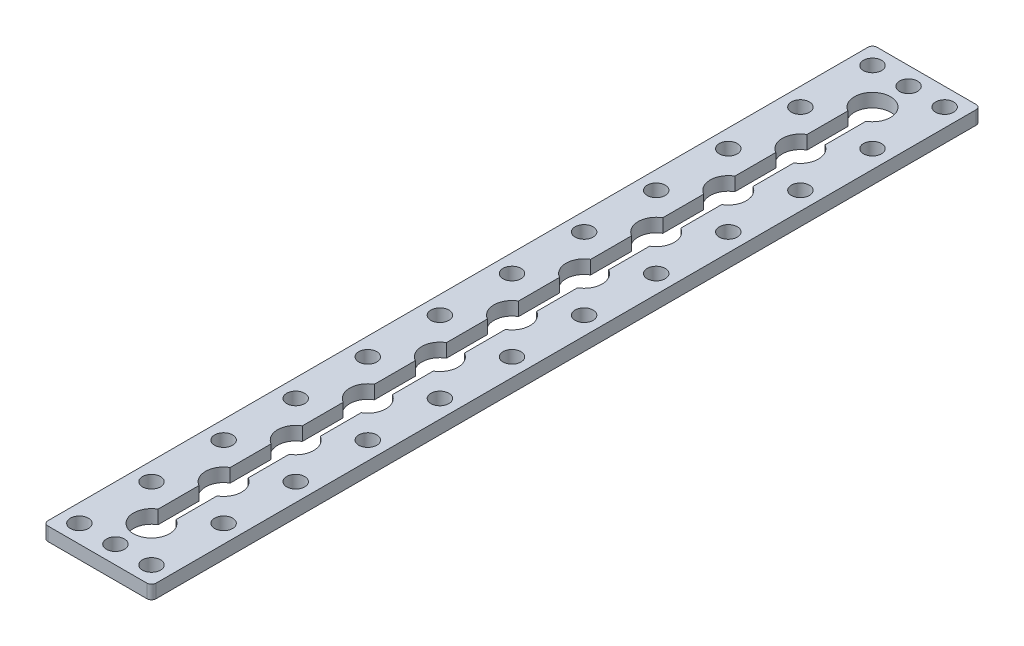
SolidWorks part; units mm, degrees
material "6061 Alloy"
ref_plane "Front Plane" through (0, 0, 0) normal (0, 0, 1) x (1, 0, 0)
ref_plane "Top Plane" through (0, 0, 0) normal (0, 1, 0) x (1, 0, 0)
ref_plane "Right Plane" through (0, 0, 0) normal (1, 0, 0) x (0, 0, -1)
sketch "Sketch1" plane through (0, 0, 0) normal (0, 1, 0) x (1, 0, 0)
  line L1 (12, -92) -> (-12, -92)
  line L2 (12, -92) -> (12, 92)
  line L3 (12, 92) -> (-12, 92)
  line L4 (-12, -92) -> (-12, 92)
  line L5 (12, -92) -> (-12, 92) construction
  line L6 (12, 92) -> (-12, -92) construction
  point P0 (0, 0)
  dimension "D1" = 184
  dimension "D2" = 24
extrude "Boss-Extrude1" add sketch "Sketch1" along normal blind 3
sketch "Sketch2" plane through (0, 3, 0) normal (0, 1, 0) x (1, 0, 0)
  line L0 (12, 92) -> (-12, 92) construction
  point P0 (-8, 88)
  point P1 (0, 88)
  point P2 (8, 88)
  point P3 (-8, 80)
  point P4 (8, 80)
  point P5 (-8, 72)
  point P6 (8, 72)
  point P7 (-8, 56)
  point P8 (8, 56)
  point P9 (8, 40)
  point P13 (8, 8)
  point P14 (-8, 8)
  point P15 (-8, 24)
  point P16 (8, 24)
  point P19 (-8, 40)
  dimension "D1" = 4
  dimension "D2" = 16
  dimension "D3" = 8
  dimension "D4" = 8
  dimension "D5" = 8
  dimension "D6" = 16
  dimension "D7" = 16
  dimension "D8" = 16
  dimension "D9" = 16
hole_wizard "Ø4.0 (4) Diameter Hole1" positions "Sketch3" profile "Sketch4" hole size "Ø4.0" standard "GB" end condition through all
sketch "Sketch3" plane through (0, 3, 0) normal (0, 1, 0) x (1, 0, 0)
  point P0 (-8, 88)
  point P3 (0, 88)
  point P6 (8, 88)
  point P15 (-8, 72)
  point P18 (-8, 56)
  point P21 (8, 56)
  point P24 (8, 72)
  point P28 (-8, 40)
  point P31 (8, 40)
  point P35 (-8, 24)
  point P38 (-8, 8)
  point P41 (8, 8)
  point P44 (8, 24)
sketch "Sketch4" plane through (-8, 3, -88) normal (1, 0, 0) x (0, 0, 1)
  line L0 (0, 0) -> (0, 3)
  line L1 (0, 3) -> (2, 3)
  line L2 (2, 3) -> (2, 0)
  line L5 (2, 0) -> (0, 0)
  line L11 (0, -6.35) -> (0, 107.95) construction
  dimension "Thru Hole Dia." = 4
  dimension "Thru Hole Depth" = 3
mirror "Mirror1" about plane through (0, 0, 0) normal (0, 0, 1) of "Ø4.0 (4) Diameter Hole1"
sketch "Sketch6" plane through (0, 3, 0) normal (0, 1, 0) x (1, 0, 0)
  point P0 (0, 80)
hole_wizard "Ø8.0 (8) Diameter Hole1" positions "Sketch7" profile "Sketch8" hole size "Ø8.0" standard "GB" end condition through all
sketch "Sketch7" plane through (0, 3, 0) normal (0, 1, 0) x (1, 0, 0)
  point P0 (0, 80)
sketch "Sketch8" plane through (0, 3, -80) normal (1, 0, 0) x (0, 0, 1)
  line L0 (0, 0) -> (0, 3)
  line L1 (0, 3) -> (4, 3)
  line L2 (4, 3) -> (4, 0)
  line L5 (4, 0) -> (0, 0)
  line L11 (0, -6.35) -> (0, 107.95) construction
  dimension "Thru Hole Dia." = 8
  dimension "Thru Hole Depth" = 3
pattern_linear "LPattern1" count 11 spacing 16 along (0, 0, 1) of "Ø8.0 (8) Diameter Hole1"
sketch "Sketch9" plane through (0, 3, 0) normal (0, 1, 0) x (1, 0, 0)
  line L0 (-12, -92) -> (12, -92) construction
  line L1 (-2, 80) -> (2, 80)
  line L2 (-2, 80) -> (-2, -80)
  line L3 (-2, -80) -> (2, -80)
  line L4 (2, 80) -> (2, -80)
  line L5 (-2, 80) -> (2, -80) construction
  line L6 (-2, -80) -> (2, 80) construction
  point P4 (0, 0)
  dimension "D1" = 4
  dimension "D2" = 12
extrude "Cut-Extrude1" cut sketch "Sketch9" against normal blind 3
fillet "Fillet1" radius 1 4 edges at (12, 1.5, -92) (-12, 1.5, -92) (12, 1.5, 92) (-12, 1.5, 92)
equation "\"D8@Sketch2\"=\"D7@Sketch2\""
equation "\"D9@Sketch2\"=\"D8@Sketch2\""
